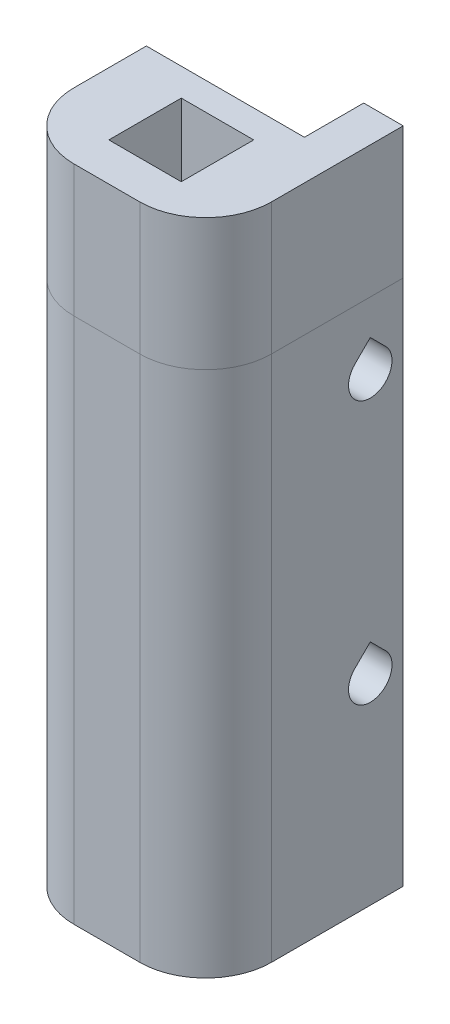
SolidWorks part; units mm, degrees
ref_plane "Front Plane" through (0, 0, 0) normal (1, 0, 0) x (0, 1, 0)
ref_plane "Top Plane" through (0, 0, 0) normal (0, 0, 1) x (0, 1, 0)
ref_plane "Right Plane" through (0, 0, 0) normal (0, 1, 0) x (-1, 0, 0)
sketch "Sketch1" plane through (0, 0, 0) normal (0, 0, 1) x (0, 1, 0)
  line L1 (-25, -7.5) -> (25, -7.5)
  line L2 (-25, -7.5) -> (-25, 7.5)
  line L3 (-25, 7.5) -> (25, 7.5)
  line L4 (25, -7.5) -> (25, 7.5)
  line L5 (-25, -7.5) -> (25, 7.5) construction
  line L6 (-25, 7.5) -> (25, -7.5) construction
  point P0 (0, 0)
  dimension "D1" = 15
  dimension "D2" = 50
extrude "Boss-Extrude1" add sketch "Sketch1" along normal blind 15 contours L3 L4 L1 L2
sketch "Sketch2" plane through (0, 25, 0) normal (0, 1, 0) x (-1, 0, 0)
  line L5 (-2.75, 12.1) -> (2.75, 12.1)
  line L6 (-7.5, 15) -> (-7.5, 0) construction
  line L10 (-7.5, 0) -> (7.5, 0) construction
  line L11 (-4.5, 0) -> (4.5, 0)
  line L12 (-4.5, 0) -> (-4.5, 4.5)
  line L13 (-4.5, 4.5) -> (4.5, 4.5)
  line L14 (4.5, 0) -> (4.5, 4.5)
  line L15 (7.5, 15) -> (7.5, 0) construction
  line L16 (-2.75, 12.1) -> (-2.75, 6.6)
  line L17 (-2.75, 6.6) -> (2.75, 6.6)
  line L18 (2.75, 12.1) -> (2.75, 6.6)
  line L19 (-7.5, 15) -> (7.5, 15) construction
  line M7 (-7.5, 0) -> (7.5, 0)
  dimension "D2" = 5.5
  dimension "D3" = 5.5
  dimension "D4" = 4.75
  dimension "D5" = 2.9
  dimension "D6" = 4.75
  dimension "D9" = 3
  dimension "D10" = 3
  dimension "D11" = 4.5
extrude "Cut-Extrude1" cut sketch "Sketch2" against normal through all contours L18 L5 L16 L17 | L14 L13 L12 M7
sketch "Sketch3" plane through (7.5, 0, 0) normal (1, 0, 0) x (0, 1, 0)
  line L0 (-40, 2.5) -> (-11.65, 2.5) construction
  line L1 (-7.6777, 2.5) -> (-8.7248, 3.547)
  line L2 (-7.6777, 2.5) -> (-8.7248, 1.453)
  line L3 (-25, 0) -> (25, 0) construction
  line L4 (-25, 15) -> (-25, 0) construction
  line L5 (0, 0) -> (0, 10.3697) construction
  line L6 (-8.35, 2.5) -> (8.35, 2.5) construction
  line L7 (11.1667, 3.6667) -> (12.3335, 2.5)
  line L8 (11.1667, 1.3333) -> (12.3335, 2.5)
  line L9 (11.65, 2.5) -> (40, 2.5) construction
  arc A0 (-8.7248, 3.547) -> (-8.7248, 1.453) centre (-10, 2.5) ccw
  arc A2 (11.1667, 1.3333) -> (11.1667, 3.6667) centre (10, 2.5) cw
  dimension "D1" = 3.3
  dimension "D4" = 15
  dimension "D5" = 45
  dimension "D2" = 2.5
  dimension "D3" = 0
  dimension "D6" = 45
extrude "Cut-Extrude2" cut sketch "Sketch3" against normal through all
sketch "Sketch4" plane through (0, 0, 15) normal (0, 0, 1) x (1, 0, 0)
  line L0 (-7.5, 15) -> (7.5, 15)
  line L1 (-7.5, -25) -> (-7.5, 25) construction
  line L2 (7.5, -25) -> (7.5, 25) construction
  line L3 (7.5, 25) -> (-7.5, 25) construction
  dimension "D1" = 10
fillet "Fillet1" radius 5 2 edges at (7.5, 0, 15) (-7.5, 0, 15)
split "Split1" trim tools "Sketch4" bodies to split 103 resulting bodies 104 105
sketch "Sketch5" plane through (0, 25, 0) normal (0, 1, 0) x (-1, 0, 0)
  line L0 (4.5, 0) -> (7.5, 0) construction
  line L1 (4.5, 4.5) -> (7.5, 4.5)
  line L2 (4.5, 4.5) -> (4.5, 0)
  line L3 (4.5, 0) -> (7.5, 0)
  line L4 (7.5, 4.5) -> (7.5, 0)
extrude "Cut-Extrude3" cut sketch "Sketch5" against normal through all
